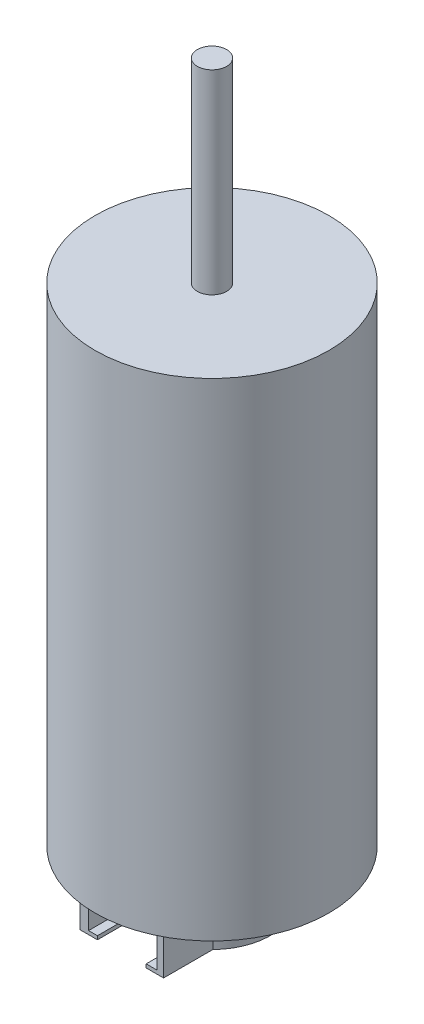
SolidWorks part; units mm, degrees
ref_plane "Front Plane" through (0, 0, 0) normal (0, 0, 1) x (1, 0, 0)
ref_plane "Top Plane" through (0, 0, 0) normal (0, 1, 0) x (1, 0, 0)
ref_plane "Right Plane" through (0, 0, 0) normal (1, 0, 0) x (0, 0, -1)
sketch "Sketch1" plane through (0, 0, 0) normal (0, 1, 0) x (1, 0, 0)
  circle A0 centre (0, 0) radius 12
extrude "Boss-Extrude1" add sketch "Sketch1" along normal blind 50
sketch "Sketch2" plane through (0, 50, 0) normal (0, 1, 0) x (1, 0, 0)
  circle A0 centre (0, 0) radius 1.5
extrude "Boss-Extrude2" add sketch "Sketch2" along normal blind 20
sketch "Sketch3" plane through (0, 0, 0) normal (0, -1, 0) x (1, 0, 0)
  line L0 (-4.2843, 4.2006) -> (-4.2843, 9.2544)
  line L1 (-4.2843, 9.2544) -> (4.2843, 9.2544)
  line L3 (4.2843, 4.2006) -> (4.2843, 9.2544)
  arc A0 (-4.2843, 4.2006) -> (4.2843, 4.2006) centre (0, 0) ccw
extrude "Boss-Extrude3" add sketch "Sketch3" along normal blind 5
sketch "Sketch4" plane through (0, 0, 9.2544) normal (0, 0, 1) x (1, 0, 0)
  line L1 (-3.4108, -0.6331) -> (3.5892, -0.6331)
  line L2 (-3.4108, -0.6331) -> (-3.4108, -4.6331)
  line L3 (-3.4108, -4.6331) -> (3.5892, -4.6331)
  line L4 (3.5892, -0.6331) -> (3.5892, -4.6331)
  line L5 (-3.4108, -0.6331) -> (3.5892, -4.6331) construction
  line L6 (-3.4108, -4.6331) -> (3.5892, -0.6331) construction
  point P0 (0.0892, -2.6331)
extrude "Cut-Extrude1" cut sketch "Sketch4" against normal blind 5
sketch "Sketch5" plane through (0, -5, 0) normal (0, -1, 0) x (1, 0, 0)
  line L0 (4.2843, 9.2544) -> (-4.2843, 9.2544) construction
  line L1 (-2.5018, 9.2544) -> (2.4982, 9.2544)
  line L2 (-2.5018, 9.2544) -> (-2.5018, 5.8037)
  line L3 (-2.5018, 5.8037) -> (2.4982, 5.8037)
  line L4 (2.4982, 9.2544) -> (2.4982, 5.8037)
  point P6 (0, 0)
  point P7 (0, 0)
extrude "Cut-Extrude2" cut sketch "Sketch5" against normal blind 0.4
